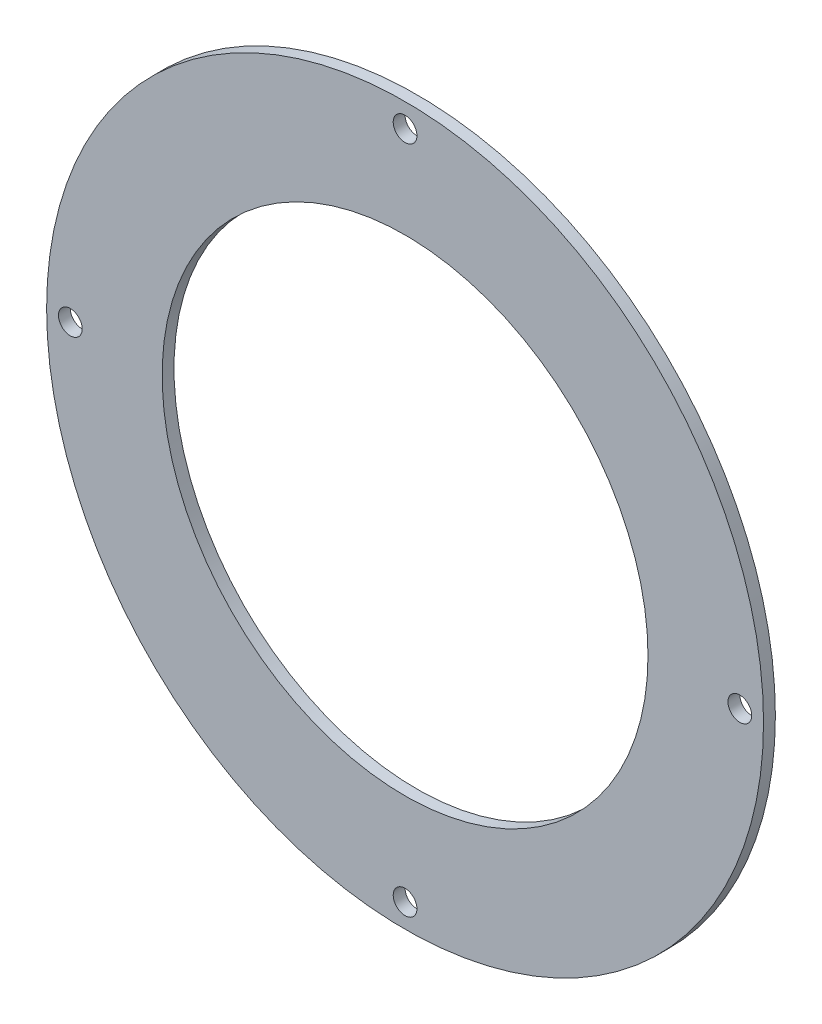
SolidWorks part; units mm, degrees
ref_plane "前视基准面" through (0, 0, 0) normal (0, 0, 1) x (1, 0, 0)
ref_plane "上视基准面" through (0, 0, 0) normal (0, 1, 0) x (1, 0, 0)
ref_plane "右视基准面" through (0, 0, 0) normal (1, 0, 0) x (0, 0, -1)
sketch "草图1" plane through (0, 0, 0) normal (0, 0, 1) x (1, 0, 0)
  line L0 (0, -52.5) -> (0, -60.5) construction
  line L1 (0, 0) -> (36.1973, 0) construction
  line L2 (0, 0) -> (39.2724, -22.6739) construction
  circle A1 centre (0, 0) radius 60.5
  circle A3 centre (0, 0) radius 52.5 construction
  circle A4 centre (0, -56.5) radius 2
  circle A5 centre (0, -56.5) radius 3.8 construction
  circle A6 centre (-56.5, 0) radius 2
  circle A7 centre (0, 56.5) radius 2
  circle A8 centre (56.5, 0) radius 2
  circle A9 centre (0, 0) radius 23.75 construction
  circle A10 centre (0, 0) radius 22.5 construction
  circle A11 centre (0, -23.75) radius 2.6
  circle A12 centre (-20.5681, 11.875) radius 2.6
  circle A13 centre (20.5681, 11.875) radius 2.6
  circle A14 centre (19.4856, -11.25) radius 2.6
  circle A15 centre (-19.4856, -11.25) radius 2.6
  circle A16 centre (0, 22.5) radius 2.6
  circle A17 centre (0, 0) radius 15.5
  dimension "D1" = 47.5
  dimension "D2" = 121
  dimension "D3" = 105
  dimension "D4" = 7.6
  dimension "D6" = 45
  dimension "D7" = 5.2
  dimension "D9" = 5.2
  dimension "D10" = 31
  dimension "D8" = 30
  dimension "D5" = 4
extrude "凸台-拉伸1" add sketch "草图1" along normal blind 2
sketch "草图2" plane through (0, 0, 2) normal (0, 0, 1) x (1, 0, 0)
  circle A0 centre (0, 0) radius 41
  dimension "D1" = 82
extrude "切除-拉伸1" cut sketch "草图2" against normal blind 10
